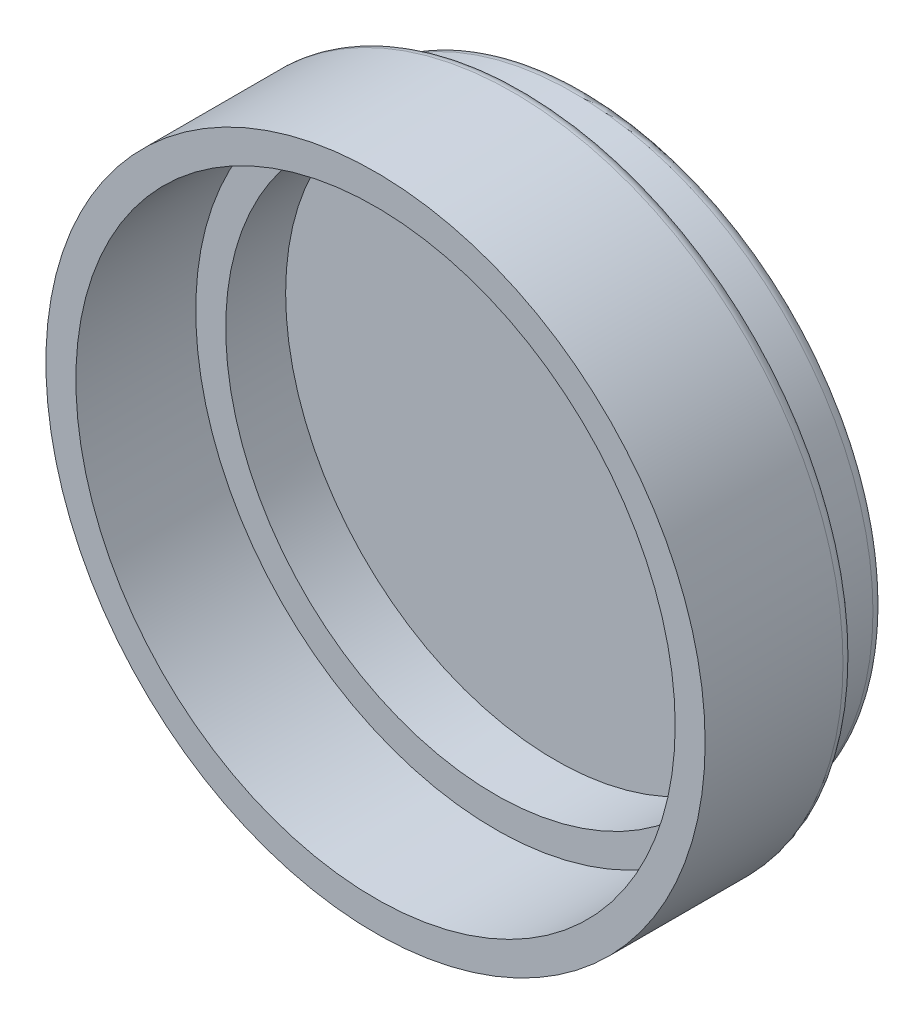
SolidWorks part; units mm, degrees
material "PVC Rígido"
ref_plane "Plano frontal" through (0, 0, 0) normal (0, 0, 1) x (1, 0, 0)
ref_plane "Plano superior" through (0, 0, 0) normal (0, 1, 0) x (1, 0, 0)
ref_plane "Plano direito" through (0, 0, 0) normal (1, 0, 0) x (0, 0, -1)
sketch "Esboço1" plane through (0, 0, 0) normal (0, 0, 1) x (1, 0, 0)
  circle A0 centre (0, 0) radius 55
  dimension "D1" = 110
extrude "Ressalto-extrusão1" add sketch "Esboço1" along normal blind 25 contours A0
sketch "Esboço2" plane through (0, 0, 0) normal (0, 0, -1) x (-1, 0, 0)
  circle A0 centre (0, 0) radius 50
extrude "Ressalto-extrusão2" add sketch "Esboço2" along normal blind 10
shell "Casca1" thickness 5
fillet "Filete2" radius 2 2 edges at (-50, 0, 0) (-50, 0, -10)
fillet "Filete3" radius 2 1 edges at (55, 0, 0)
